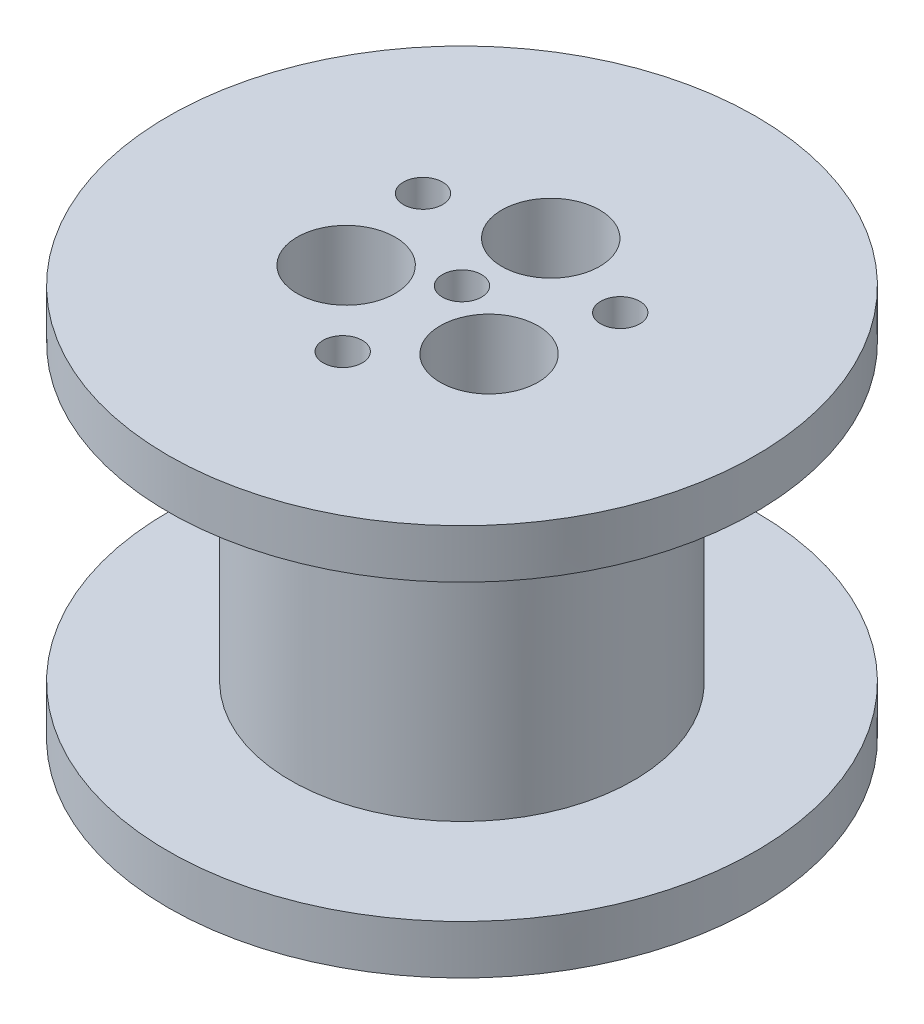
SolidWorks part; units mm, degrees
ref_plane "Front Plane" through (0, 0, 0) normal (0, 0, 1) x (1, 0, 0)
ref_plane "Top Plane" through (0, 0, 0) normal (0, 1, 0) x (1, 0, 0)
ref_plane "Right Plane" through (0, 0, 0) normal (1, 0, 0) x (0, 0, -1)
sketch "Sketch1" plane through (0, 0, 0) normal (0, 1, 0) x (1, 0, 0)
  circle A0 centre (0, 0) radius 30
extrude "Boss-Extrude1" add sketch "Sketch1" along normal blind 40
sketch "Sketch2" plane through (0, 0, 0) normal (0, -1, 0) x (1, 0, 0)
  circle A1 centre (0, 0) radius 17.5
extrude "Cut-Extrude1" cut sketch "Sketch2" against normal blind 30 from offset 5 flip side to cut offset against normal yes
sketch "Sketch3" plane through (0, 0, 0) normal (0, -1, 0) x (1, 0, 0)
  circle A0 centre (0, 0) radius 2
extrude "Cut-Extrude2" cut sketch "Sketch3" against normal through all
sketch "Sketch4" plane through (0, 0, 0) normal (0, -1, 0) x (1, 0, 0)
  line L1 (-14.8275, -9.2948) -> (15.4633, -8.1936)
  line L2 (15.4633, -8.1936) -> (-0.6358, 17.4884)
  line L3 (-0.6358, 17.4884) -> (-14.8275, -9.2948)
  circle A0 centre (0, 0) radius 8.75 construction
  circle A1 centre (7.4138, 4.6474) radius 5
  circle A2 centre (0.3179, -8.7442) radius 5
  circle A3 centre (-7.7317, 4.0968) radius 5
  point P1 (7.4138, 4.6474)
  point P7 (0.3179, -8.7442)
  point P8 (-7.7317, 4.0968)
extrude "Cut-Extrude3" cut sketch "Sketch4" against normal through all contours L1 A2 | L1 A2 | L2 A1 | L2 A1 | L3 A3 | L3 A3
sketch "Sketch5" plane through (0, 5, 0) normal (0, 1, 0) x (1, 0, 0)
  circle A0 centre (-15.3397, 8.4227) radius 2
  circle A1 centre (0, 0) radius 17.5 construction
extrude "Cut-Extrude4" cut sketch "Sketch5" against normal up to next
sketch "Sketch8" plane through (0, 40, 0) normal (0, 1, 0) x (1, 0, 0)
  line L0 (0, 0) -> (-11.7462, 7.1477) construction
  line L1 (11.7462, -7.1477) -> (12.0632, 6.5987)
  line L2 (12.0632, 6.5987) -> (0.317, 13.7463)
  line L3 (0.317, 13.7463) -> (-11.7462, 7.1477)
  line L4 (-11.7462, 7.1477) -> (-12.0632, -6.5987)
  line L5 (-12.0632, -6.5987) -> (-0.317, -13.7463)
  line L6 (-0.317, -13.7463) -> (11.7462, -7.1477)
  line L7 (0, 0) -> (12.0632, 6.5987) construction
  line L8 (0, 0) -> (-0.317, -13.7463) construction
  circle A0 centre (0, 0) radius 13.75
  circle A2 centre (0, 0) radius 11.9078 construction
  circle A3 centre (-0.2745, -11.9047) radius 2
  circle A4 centre (10.4464, 5.7143) radius 2
  circle A5 centre (-10.172, 6.1898) radius 2
  point P5 (11.7462, -7.1477)
  dimension "D1" = 4
  dimension "D2" = 4
  dimension "D3" = 4
extrude "Cut-Extrude5" cut sketch "Sketch8" along direction (0, 1, 0) on the side against the normal through all contours A4 | A5 | L6 A3 L5 | A0 A3 L6 | L5 A3 A0 | A0 A3 | A0 A5 L4 | L3 A5 A0 | A0 A5 | L1 A4 A0 | A0 A4 L2 | A0 A4
sketch "Sketch9" plane through (0, 40, 0) normal (0, 1, 0) x (1, 0, 0)
  circle A0 centre (0, 0) radius 30
extrude "Cut-Extrude6" [suppressed] cut sketch "Sketch9" against normal blind 20
